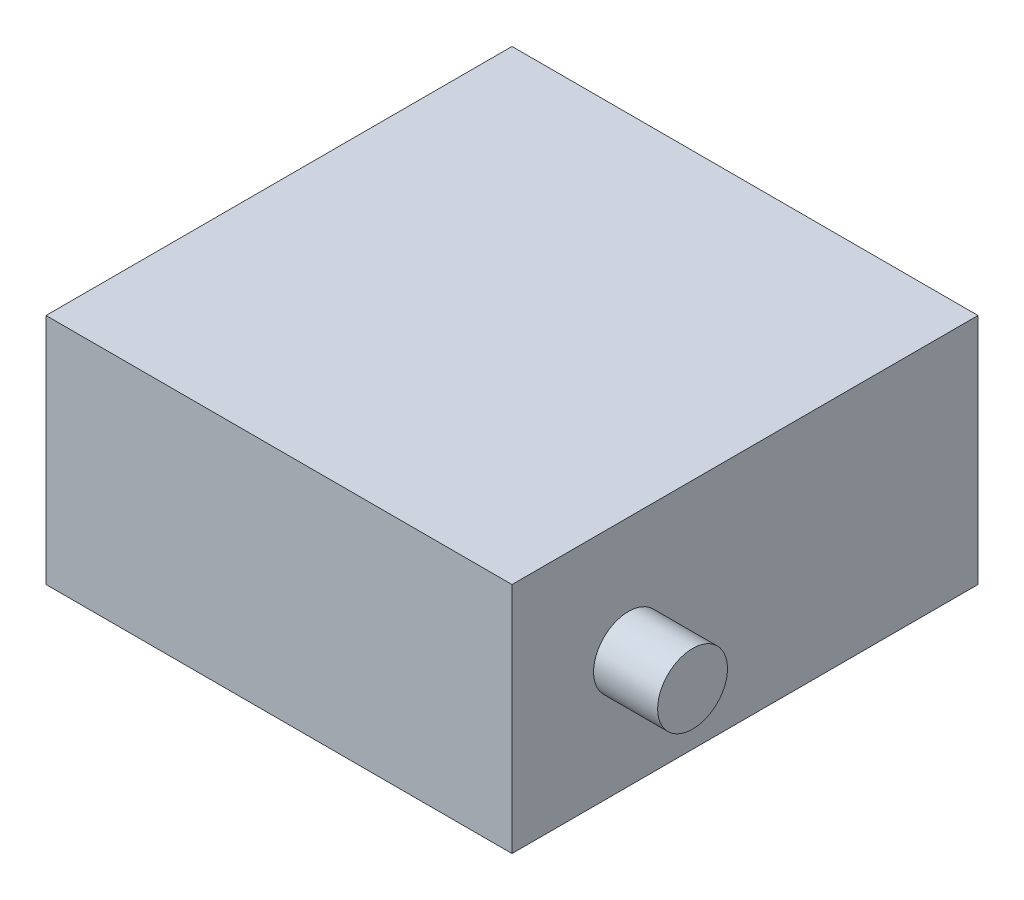
SolidWorks part; units mm, degrees
ref_plane "Alzado" through (0, 0, 0) normal (0, 0, 1) x (1, 0, 0)
ref_plane "Planta" through (0, 0, 0) normal (0, 1, 0) x (1, 0, 0)
ref_plane "Vista lateral" through (0, 0, 0) normal (1, 0, 0) x (0, 0, -1)
sketch "Croquis1" plane through (0, 0, 0) normal (0, 0, 1) x (1, 0, 0)
  line L1 (-20, -10) -> (20, -10)
  line L2 (-20, -10) -> (-20, 10)
  line L3 (-20, 10) -> (20, 10)
  line L4 (20, -10) -> (20, 10)
  line L5 (-20, -10) -> (20, 10) construction
  line L6 (-20, 10) -> (20, -10) construction
  point P0 (0, 0)
  dimension "D1" = 20
  dimension "D2" = 40
extrude "Saliente-Extruir1" add sketch "Croquis1" along normal blind 40
sketch "Croquis2" plane through (-20, 0, 0) normal (-1, 0, 0) x (0, 0, 1)
  line L0 (40, 0) -> (0, 0) construction
  line L1 (40, 10) -> (40, -10) construction
  line L2 (0, 10) -> (0, -10) construction
  circle A0 centre (30, 0) radius 3
  dimension "D1" = 10
  dimension "D2" = 6
extrude "Saliente-Extruir2" add sketch "Croquis2" along normal blind 5.5
mirror "Simetría1" about plane through (0, 0, 0) normal (1, 0, 0) of "Saliente-Extruir2"
